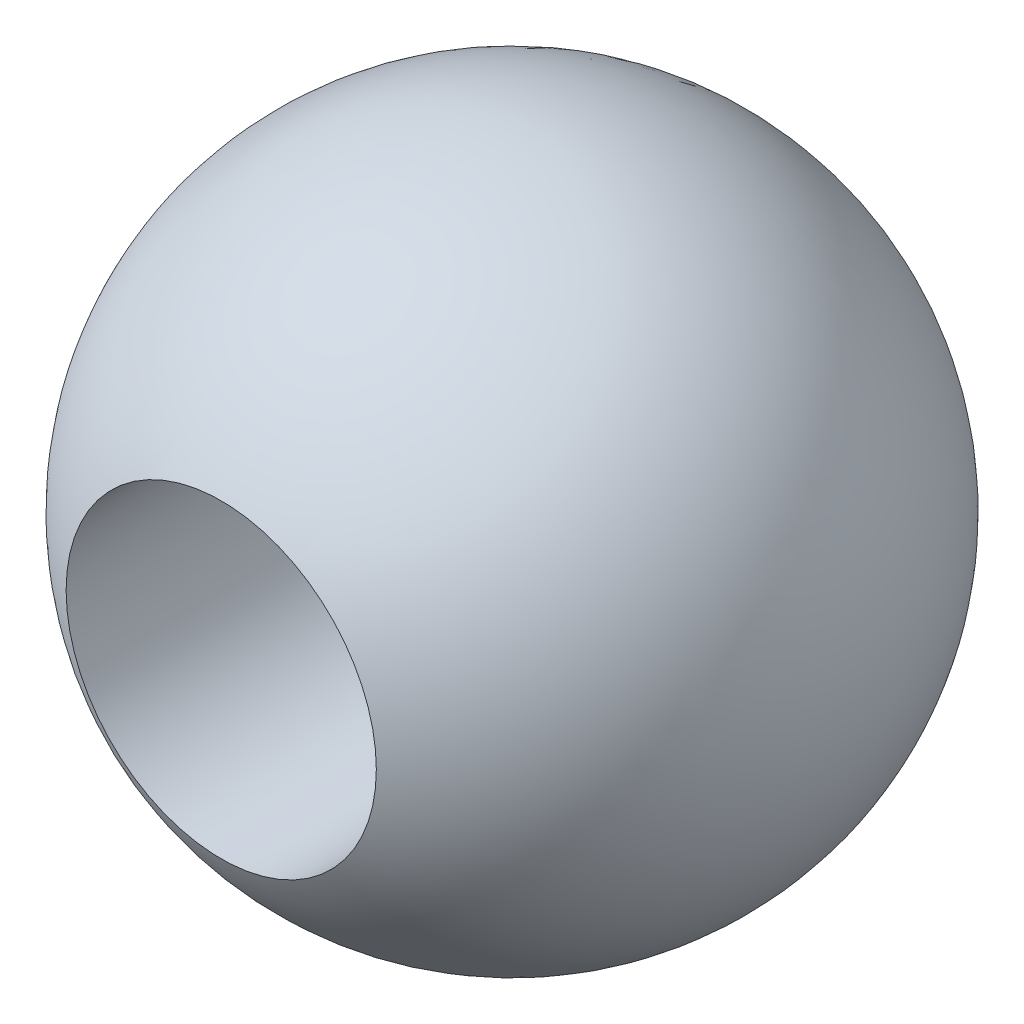
SolidWorks part; units mm, degrees
ref_plane "Front Plane" through (0, 0, 0) normal (0, 0, 1) x (1, 0, 0)
ref_plane "Top Plane" through (0, 0, 0) normal (0, 1, 0) x (1, 0, 0)
ref_plane "Right Plane" through (0, 0, 0) normal (1, 0, 0) x (0, 0, -1)
sketch "Sketch1" plane through (0, 0, 0) normal (0, 0, 1) x (1, 0, 0)
  line L0 (-8.5, 0) -> (8.5, 0)
  arc A0 (-8.5, 0) -> (8.5, 0) centre (0, 0) cw
  point P4 (0, 0)
  dimension "D2" = 8.5
  dimension "D1" = 17
revolve "Revolve1" add sketch "Sketch1" angle 360 about L0
sketch "Sketch2" plane through (0, 0, 0) normal (0, 0, 1) x (1, 0, 0)
  circle A0 centre (0, 0) radius 4
  dimension "D1" = 8
extrude "Cut-Extrude1" cut sketch "Sketch2" against normal through all both and the other way through all
sketch "Sketch3" plane through (0, 0, 0) normal (0, 1, 0) x (1, 0, 0)
  circle A0 centre (0, 0) radius 1.3
  dimension "D1" = 2.6
extrude "Cut-Extrude2" cut sketch "Sketch3" against normal through all
